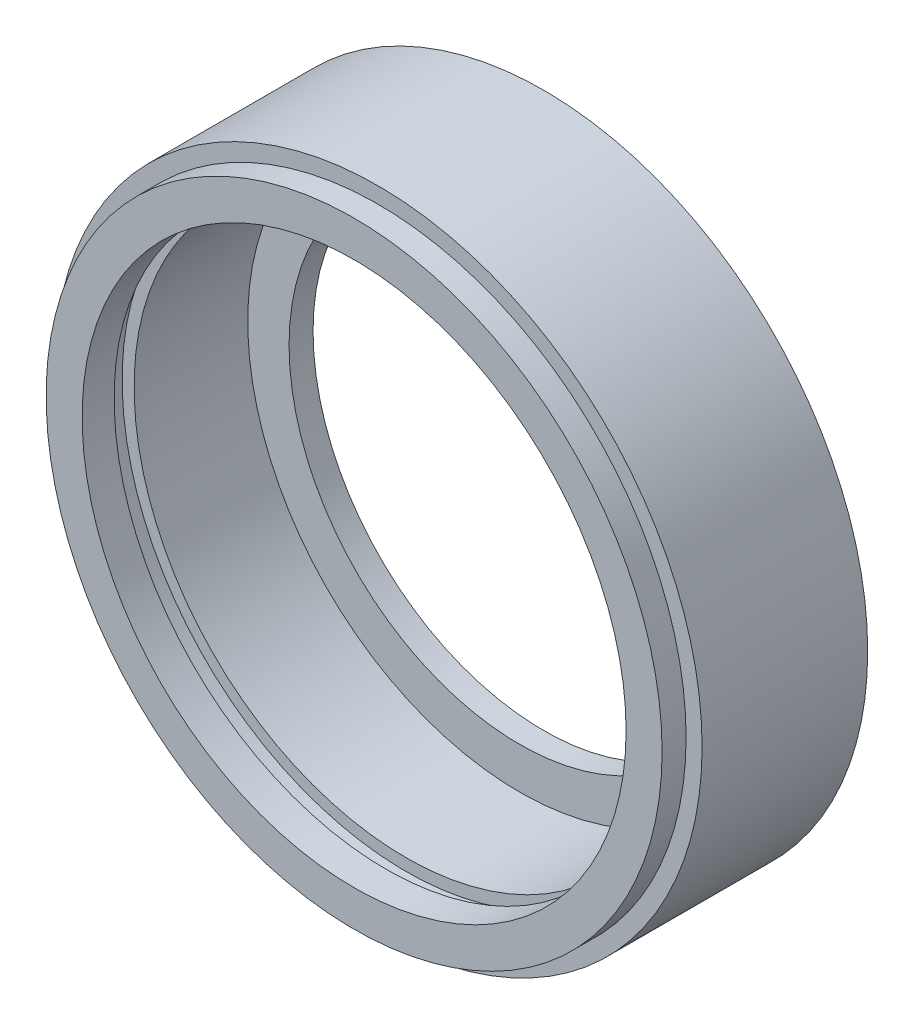
SolidWorks part; units mm, degrees
material "СТ3КП"
ref_plane "Спереди" through (0, 0, 0) normal (0, 0, 1) x (1, 0, 0)
ref_plane "Сверху" through (0, 0, 0) normal (0, 1, 0) x (1, 0, 0)
ref_plane "Справа" through (0, 0, 0) normal (1, 0, 0) x (0, 0, -1)
sketch "Эскиз1" plane through (0, 0, 0) normal (1, 0, 0) x (0, 0, -1)
  line L0 (0, 0) -> (0, 40.5) construction
  line L1 (-23.7, 0) -> (-23.7, 75) construction
  line L2 (-23.7, 38.5) -> (-20.7, 38.5) construction
  line L3 (-20.7, 38.5) -> (-20.7, 40.5) construction
  line L4 (-23.7, 40.5) -> (0, 40.5) construction
  line L5 (0, 28.8333) -> (0, 40.5)
  line L6 (-23.7, 34) -> (-23.7, 38.5)
  line L7 (-23.7, 38.5) -> (-20.7, 38.5)
  line L8 (-20.7, 38.5) -> (-20.7, 40.5)
  line L9 (-20.7, 40.5) -> (0, 40.5)
  line L10 (-23.7, 34) -> (-19.7, 34)
  line L11 (-3, 34) -> (-3, 28.8333)
  line L12 (-3, 28.8333) -> (0, 28.8333)
  line L13 (-4.5, 34) -> (-16.5, 34) construction
  line L14 (-3, -32.5) -> (-3, 32.5) construction
  line L15 (-19.7, 35.5) -> (-19.7, -34.3561) construction
  line L16 (-19.7, 35.5) -> (-19.7, 34)
  line L17 (-19.7, 35.5) -> (-17.2, 35.5)
  line L18 (-17.2, 35.5) -> (-17.2, 34)
  line L19 (-17.2, 34) -> (-3, 34)
  line L20 (-3, 28.8333) -> (-5.5, 28.8333) construction
  line L21 (-1010.5, 0) -> (48989.5, 0) construction
  dimension "D1" = 2.5
revolve "Повернуть1" add sketch "Эскиз1" angle 360 about L21
